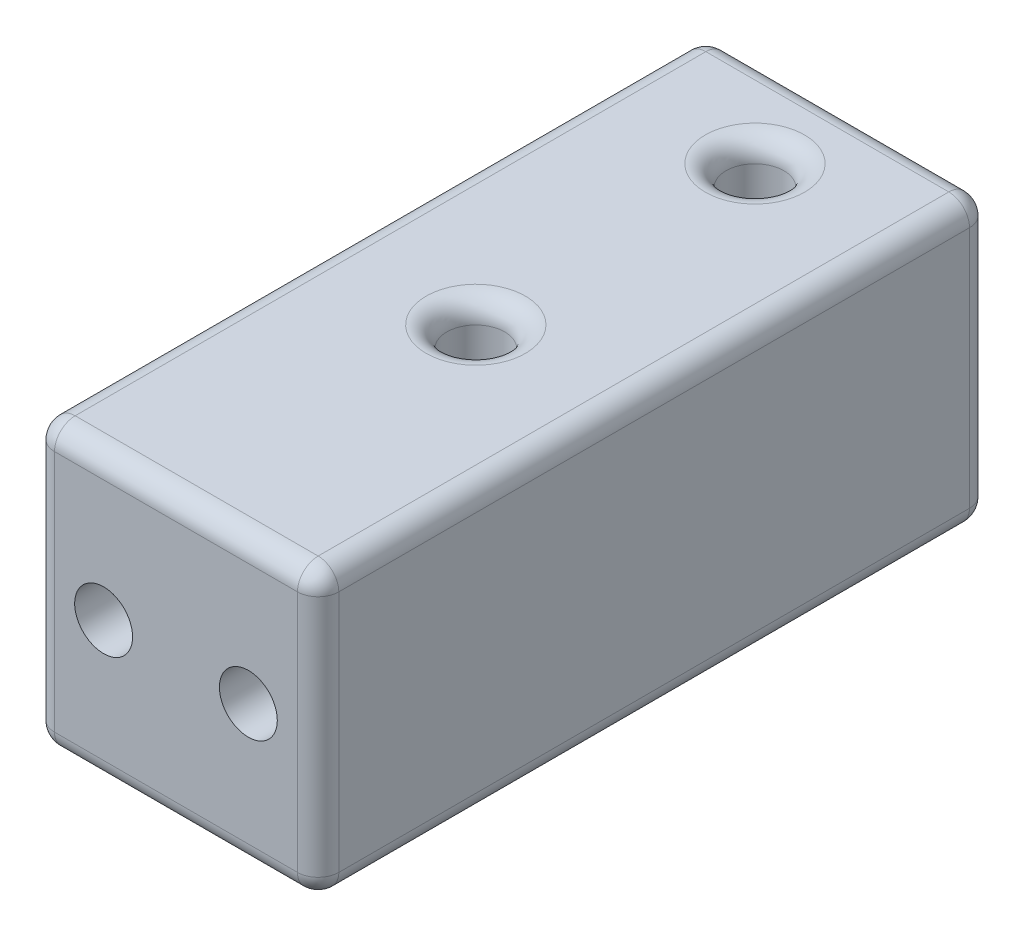
SolidWorks part; units mm, degrees
ref_plane "Front Plane" through (0, 0, 0) normal (0, 0, 1) x (1, 0, 0)
ref_plane "Top Plane" through (0, 0, 0) normal (0, 1, 0) x (1, 0, 0)
ref_plane "Right Plane" through (0, 0, 0) normal (1, 0, 0) x (0, 0, -1)
sketch "Sketch1" plane through (0, 0, 0) normal (0, 0, 1) x (1, 0, 0)
  line L1 (-6.875, -6.875) -> (6.875, -6.875)
  line L2 (-6.875, -6.875) -> (-6.875, 6.875)
  line L3 (-6.875, 6.875) -> (6.875, 6.875)
  line L4 (6.875, -6.875) -> (6.875, 6.875)
  line L5 (-6.875, -6.875) -> (6.875, 6.875) construction
  line L6 (-6.875, 6.875) -> (6.875, -6.875) construction
  point P0 (0, 0)
  dimension "D1" = 13.75
extrude "Boss-Extrude1" add sketch "Sketch1" along normal blind 14.5 and the other way blind 18
sketch "Sketch2" plane through (0, 0, 0) normal (0, 1, 0) x (1, 0, 0)
  circle A0 centre (0, 0) radius 1.4
  arc A3 (0, 14.525) -> (0, 12.475) centre (0, 13.5) ccw construction
  arc A4 (0, 14.525) -> (0, 12.475) centre (0, 13.5) ccw construction
  circle A5 centre (0, 13.5) radius 1.4
  dimension "D1" = 2.8
  dimension "D2" = 2.8
extrude "Cut-Extrude1" cut sketch "Sketch2" against normal through all and the other way through all
fillet "Fillet1" radius 1 12 edges at (0, 6.875, -18) (-6.875, 0, -18) (0, -6.875, -18) (6.875, 0, -18) (0, -6.875, 14.5) (-6.875, 0, 14.5) (0, 6.875, 14.5) (6.875, 0, 14.5) (-6.875, -6.875, -1.75) (6.875, -6.875, -1.75) (-6.875, 6.875, -1.75) (6.875, 6.875, -1.75)
fillet "Fillet2" radius 1 4 edges at (0, 6.875, -12.1) (0, -6.875, -12.1) (0, -6.875, 1.4) (0, 6.875, 1.4)
sketch "Sketch3" plane through (0, 0, 14.5) normal (0, 0, 1) x (1, 0, 0)
  line L0 (-3.5, 0) -> (3.5, 0) construction
  circle A1 centre (-3.5, 0) radius 1.4
  circle A2 centre (3.5, 0) radius 1.4
  dimension "D1" = 2.8
  dimension "D2" = 7
extrude "Cut-Extrude2" cut sketch "Sketch3" against normal through all
